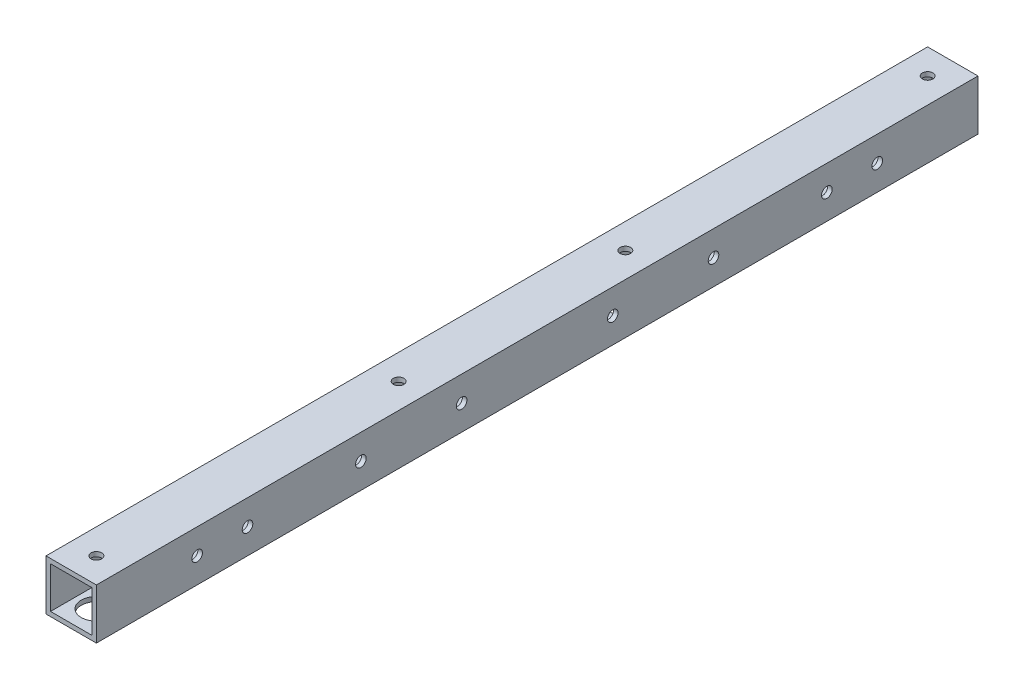
SolidWorks part; units mm, degrees
material "6061-T6 (SS)"
ref_plane "前视基准面" through (0, 0, 0) normal (0, 0, 1) x (1, 0, 0)
ref_plane "上视基准面" through (0, 0, 0) normal (0, 1, 0) x (1, 0, 0)
ref_plane "右视基准面" through (0, 0, 0) normal (1, 0, 0) x (0, 0, -1)
sketch "草图1" plane through (0, 0, 0) normal (0, 0, 1) x (1, 0, 0)
  line L1 (0, 0) -> (20, 0)
  line L2 (0, 0) -> (0, 20)
  line L6 (0, 20) -> (20, 20)
  line L7 (20, 20) -> (20, 0)
  line L8 (1.8, 1.8) -> (18.2, 1.8)
  line L9 (18.2, 18.2) -> (18.2, 1.8)
  line L10 (1.8, 18.2) -> (18.2, 18.2)
  line L11 (1.8, 1.8) -> (1.8, 18.2)
  dimension "A" = 20
  dimension "B" = 20
  dimension "T" = 1.8
sketch "草图2" plane through (0, 0, 0) normal (1, 0, 0) x (0, 0, -1)
  line L0 (0, 0) -> (350, 0) construction
  dimension "L" = 350
sketch "草图3" plane through (0, 0, 0) normal (0, 0, 1) x (1, 0, 0)
  line L0 (1.8, 1.8) -> (18.2, 1.8) construction
  line L1 (18.2, 18.2) -> (18.2, 1.8) construction
  line L2 (1.8, 18.2) -> (18.2, 18.2) construction
  line L3 (1.8, 1.8) -> (1.8, 18.2) construction
  line L10 (0, 0) -> (20, 0) construction
  line L11 (20, 20) -> (20, 0) construction
  line L12 (0, 20) -> (20, 20) construction
  line L13 (0, 0) -> (0, 20) construction
  line L14 (1.8, 1.8) -> (18.2, 1.8)
  line L15 (18.2, 18.2) -> (18.2, 1.8)
  line L16 (1.8, 18.2) -> (18.2, 18.2)
  line L17 (1.8, 1.8) -> (1.8, 18.2)
  line L18 (0, 0) -> (20, 0)
  line L19 (20, 20) -> (20, 0)
  line L20 (0, 20) -> (20, 20)
  line L21 (0, 0) -> (0, 20)
extrude "凸台-拉伸1" add sketch "草图3" against normal up to vertex (350 mm away) up to point (0, 0, -350)
sketch "草图4" plane through (20, 0, 0) normal (1, 0, 0) x (0, 0, -1)
  line L0 (350, 0) -> (0, 0) construction
  line L1 (0, 0) -> (0, 20) construction
  point P0 (40, 10)
  point P1 (60, 10)
  dimension "D1" = 10
  dimension "D2" = 10
  dimension "D3" = 40
  dimension "D4" = 20
ref_plane "基准面1" through (0, 0, -175) normal (0, 0, 1) x (1, 0, 0)
hole_wizard "Ø4.2 (4.2) 直径孔1" positions "3D草图1" profile "草图5" hole size "Ø4.2" standard "GB" end condition through all
sketch3d "3D草图1"
  point P0 (20, 10, -60)
  point P3 (20, 10, -40)
sketch "草图5" plane through (20, 10, -60) normal (0, 1, 0) x (0, 0, -1)
  line L0 (0, 0) -> (0, 20)
  line L1 (0, 20) -> (2.1, 20)
  line L2 (2.1, 20) -> (2.1, 0)
  line L5 (2.1, 0) -> (0, 0)
  line L11 (0, -6.35) -> (0, 107.95) construction
  dimension "通孔孔直径" = 4.2
  dimension "通孔孔深度" = 20
mirror "镜向1" about plane through (0, 0, -175) normal (0, 0, 1) of "Ø4.2 (4.2) 直径孔1"
sketch "草图6" plane through (20, 0, 0) normal (1, 0, 0) x (0, 0, -1)
  line L0 (350, 0) -> (0, 0) construction
  line L1 (175, 11) -> (175, -11) construction
  point P0 (145, 10)
  point P9 (105, 10)
  dimension "D1" = 10
  dimension "D2" = 30
  dimension "D4" = 40
  dimension "D3" = 2
hole_wizard "Ø4.2 (4.2) 直径孔2" positions "3D草图2" profile "草图7" hole size "Ø4.2" standard "GB" end condition through all
sketch3d "3D草图2"
  point P0 (20, 10, -145)
  point P3 (20, 10, -105)
sketch "草图7" plane through (20, 10, -145) normal (0, 1, 0) x (0, 0, -1)
  line L0 (0, 0) -> (0, 20)
  line L1 (0, 20) -> (2.1, 20)
  line L2 (2.1, 20) -> (2.1, 0)
  line L5 (2.1, 0) -> (0, 0)
  line L11 (0, -6.35) -> (0, 107.95) construction
  dimension "通孔孔直径" = 4.2
  dimension "通孔孔深度" = 20
mirror "镜向2" about plane through (0, 0, -175) normal (0, 0, 1) of "Ø4.2 (4.2) 直径孔2"
sketch "草图11" plane through (0, 0, 0) normal (0, -1, 0) x (1, 0, 0)
  line L0 (20, -350) -> (20, 0) construction
  line L1 (0, 0) -> (20, 0) construction
  line L2 (0, -350) -> (20, -350) construction
  circle A0 centre (10, -10) radius 6
  circle A1 centre (10, -340) radius 6
  dimension "D1" = 12
  dimension "D4" = 12
  dimension "D5" = 10
  dimension "D6" = 10
  dimension "D2" = 10
  dimension "D3" = 10
extrude "切除-拉伸2" cut sketch "草图11" against normal up to next
sketch "草图12" plane through (0, 20, 0) normal (0, 1, 0) x (1, 0, 0)
  line L0 (20, 350) -> (20, 0) construction
  line L1 (20, 0) -> (0, 0) construction
  line L2 (20, 350) -> (0, 350) construction
  line L3 (0, 350) -> (0, 0) construction
  point P0 (10, 10)
  point P5 (10, 340)
  dimension "D1" = 10
  dimension "D2" = 10
  dimension "D3" = 10
  dimension "D4" = 10
hole_wizard "Ø4.2 (4.2) 直径孔4" positions "3D草图4" profile "草图13" hole size "Ø4.2" standard "GB" end condition through all
sketch3d "3D草图4"
  point P0 (10, 20, -340)
  point P3 (10, 20, -10)
sketch "草图13" plane through (10, 20, -340) normal (1, 0, 0) x (0, 0, 1)
  line L0 (0, 0) -> (0, 20)
  line L1 (0, 20) -> (2.1, 20)
  line L2 (2.1, 20) -> (2.1, 0)
  line L5 (2.1, 0) -> (0, 0)
  line L11 (0, -6.35) -> (0, 107.95) construction
  dimension "通孔孔直径" = 4.2
  dimension "通孔孔深度" = 20
sketch "草图14" plane through (0, 20, 0) normal (0, 1, 0) x (1, 0, 0)
  line L0 (20, 350) -> (20, 0) construction
  line L1 (-11, 175) -> (11, 175) construction
  point P0 (10, 220)
  point P5 (10, 130)
  dimension "D1" = 10
  dimension "D2" = 45
hole_wizard "Ø4.2 (4.2) 直径孔5" positions "3D草图5" profile "草图15" hole size "Ø4.2" standard "GB" end condition through all
sketch3d "3D草图5"
  point P0 (10, 20, -220)
  point P3 (10, 20, -130)
sketch "草图15" plane through (10, 20, -220) normal (1, 0, 0) x (0, 0, 1)
  line L0 (0, 0) -> (0, 20)
  line L1 (0, 20) -> (2.1, 20)
  line L2 (2.1, 20) -> (2.1, 0)
  line L5 (2.1, 0) -> (0, 0)
  line L11 (0, -6.35) -> (0, 107.95) construction
  dimension "通孔孔直径" = 4.2
  dimension "通孔孔深度" = 20
sketch "草图16" plane through (0, 0, 0) normal (0, -1, 0) x (1, 0, 0)
  circle A0 centre (10, -130) radius 6
  circle A1 centre (10, -220) radius 6
  dimension "D1" = 12
  dimension "D2" = 12
extrude "切除-拉伸3" cut sketch "草图16" against normal up to next
